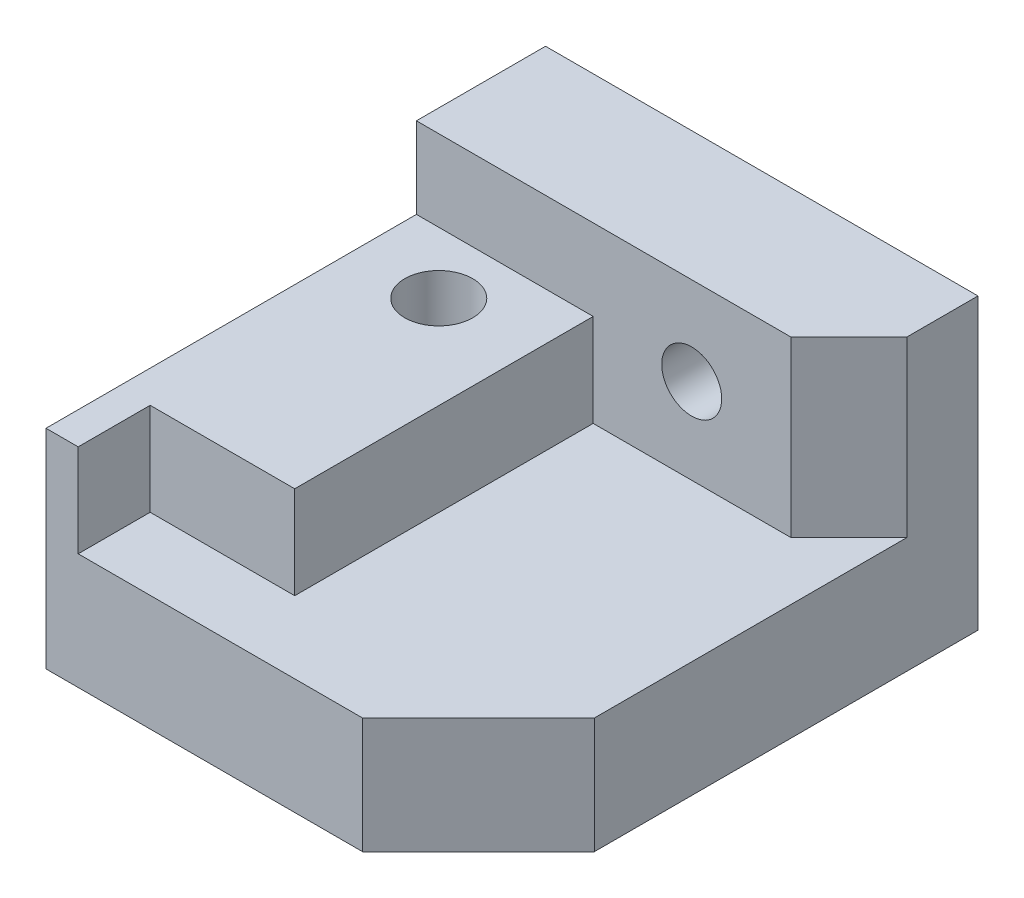
SolidWorks part; units mm, degrees
ref_plane "Front Plane" through (0, 0, 0) normal (0, 0, 1) x (1, 0, 0)
ref_plane "Plane 1" through (0, 0, 0) normal (0, 1, 0) x (1, 0, 0)
ref_plane "Right Plane" through (0, 0, 0) normal (1, 0, 0) x (0, 0, -1)
sketch "Sketch1" plane through (0, 0, 0) normal (0, 1, 0) x (1, 0, 0)
  line L0 (27.3462, 0) -> (37.3462, 10)
  line L1 (0, 0) -> (27.3462, 0)
  line L2 (0, 0) -> (0, 43.1388)
  line L3 (0, 43.1388) -> (37.3462, 43.1388)
  line L4 (37.3462, 10) -> (37.3462, 43.1388)
  line L10 (0, 43.1388) -> (37.3462, 43.1388)
  line L11 (0, 43.1388) -> (0, 33.1388)
  line L12 (0, 33.1388) -> (37.3462, 33.1388)
  line L13 (37.3462, 43.1388) -> (37.3462, 33.1388)
  point P3 (37.3462, 0)
  dimension "D1" = 10
extrude "Boss-Extrude1" add sketch "Sketch1" along normal blind 10 contours L4 L3 L2 L1 L0
sketch3d "3DSketch1"
  line L1 (0, 10, -42.0145) -> (37.3462, 10, -42.0145)
  line L2 (0, 10, -42.0145) -> (0, 10, -32.0145)
  line L3 (0, 10, -32.0145) -> (32.3462, 10, -32.0145)
  line L4 (37.3462, 10, -42.0145) -> (37.3462, 10, -37.0145)
  line L7 (0, 10, -32.0145) -> (15.2646, 10, -32.0145)
  line L8 (0, 10, -32.0145) -> (0, 10, 0)
  line L9 (0, 10, 0) -> (15.2646, 10, 0)
  line L10 (15.2646, 10, -32.0145) -> (15.2646, 10, 0)
  line L14 (32.3462, 10, -32.0145) -> (37.3462, 10, -37.0145)
  point P1 (37.3462, 10, -32.0145)
  dimension "D1" = 10
  dimension "D2" = 10
extrude "Boss-Extrude2" add sketch "3DSketch1" along direction (0, 1, 0) on the side of the normal blind 8 contours L8 L7 L10 L9
ref_plane "Plane1" through (0, 10, 0) normal (0, 1, 0) x (1, 0, 0)
sketch "Sketch2" plane through (0, 0, 0) normal (0, 1, 0) x (1, 0, 0)
  line L1 (37.3462, 10) -> (37.3462, 43.1388) construction
  line L6 (0, 43.1388) -> (37.3462, 43.1388)
  line L7 (0, 43.1388) -> (0, 31.9884)
  line L8 (0, 31.9884) -> (32.3462, 31.9884)
  line L9 (37.3462, 43.1388) -> (37.3462, 36.9884)
  line L10 (32.3462, 31.9884) -> (37.3462, 36.9884)
  point P1 (37.3462, 31.9884)
extrude "Boss-Extrude4" add sketch "Sketch2" along normal blind 25 contours L7 L6 L9 L10 L8
sketch "Sketch3" plane through (0, 18, 0) normal (0, 1, 0) x (1, 0, 0)
  line L1 (15.2646, 0) -> (2.7806, 0)
  line L2 (15.2646, 0) -> (15.2646, 6.2138)
  line L3 (15.2646, 6.2138) -> (2.7806, 6.2138)
  line L4 (2.7806, 0) -> (2.7806, 6.2138)
extrude "Cut-Extrude1" cut sketch "Sketch3" against normal blind 8
sketch "Sketch7" plane through (0, 18, 0) normal (0, 1, 0) x (1, 0, 0)
  circle A0 centre (7.2348, 26.6815) radius 2.934
extrude "Cut-Extrude4" cut sketch "Sketch7" against normal blind 18
sketch "Sketch8" plane through (0, 0, -31.9884) normal (0, 0, 1) x (1, 0, 0)
  circle A1 centre (23.7733, 17.3848) radius 2.59
extrude "Cut-Extrude5" cut sketch "Sketch8" against normal blind 18
